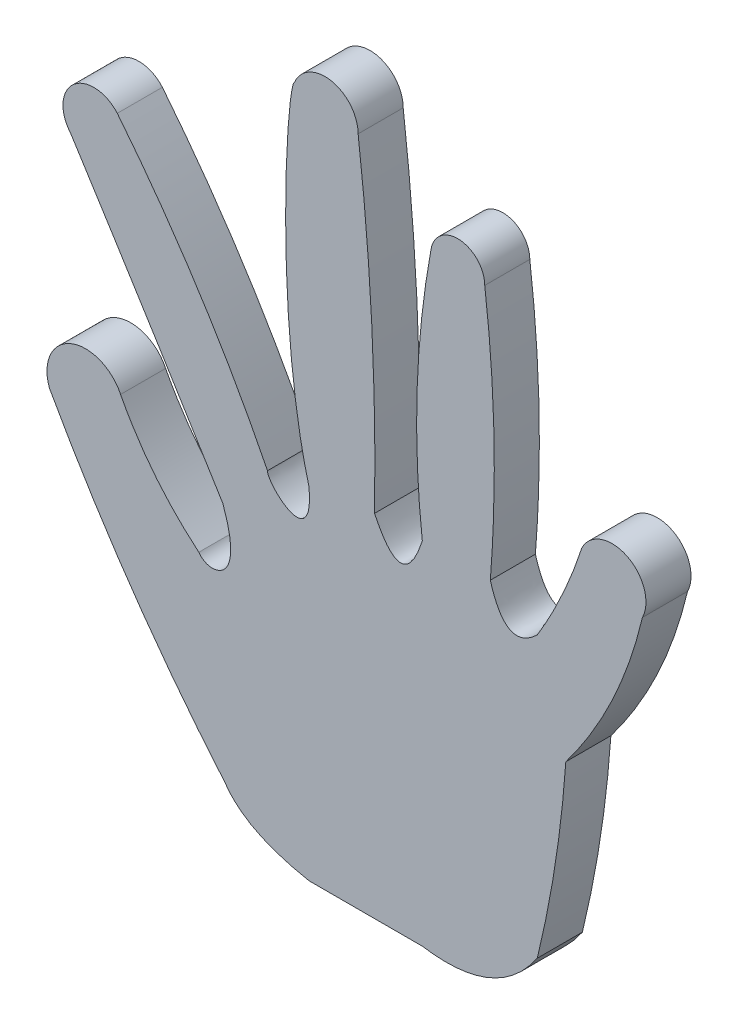
SolidWorks part; units mm, degrees
ref_plane "Alzado" through (0, 0, 0) normal (0, 0, 1) x (1, 0, 0)
ref_plane "Planta" through (0, 0, 0) normal (0, 1, 0) x (1, 0, 0)
ref_plane "Vista lateral" through (0, 0, 0) normal (1, 0, 0) x (0, 0, -1)
sketch "Croquis1" plane through (0, 0, 0) normal (0, 0, 1) x (1, 0, 0)
  line L2 (6700.2438, -5767.9046) -> (6700.2438, -4928.6598)
  line L4 (379.8796, -6850.5261) -> (423.4568, -6912.9739)
  line L11 (6128.0168, 5985.3068) -> (6128.0168, 5601.9321)
  line L12 (2230.7034, -7786.8151) -> (4743.0538, -7786.8151)
  arc A0 (-3529.5138, -1202.2335) -> (-1951.8181, -532.5527) centre (-2727.0904, -899.3757) cw
  arc A1 (-3063.1145, 3936.7407) -> (-2024.3345, 4833.6116) centre (-2543.7245, 4385.1762) cw
  arc A2 (1907.6748, 7398.1559) -> (3318.7775, 7110.1003) centre (2583.665, 7109.3167) cw
  arc A3 (4937.6033, 5708.7587) -> (6128.0168, 5601.9321) centre (5528.0168, 5601.9321) cw
  arc A4 (8283.2924, 1638.8146) -> (9626.3211, 970.7772) centre (8954.8068, 1304.7959) cw
  arc A5 (-216.138, -2695.3683) -> (389.7191, -2690.6828) centre (85.1825, -2485.1012) ccw
  parabola Q0 (1307.8944, -368.1416) -> (-2024.3345, 4833.6116) focus (-12498.1898, -5525.2093) apex (-237.4606, 2347.6576) construction
  spline S0 degree 2 poles (316.998, -1491.0681) (625.9687, -2340.7163) (389.7191, -2690.6828) knots 0 0 0 0.430746 0.430746 0.430746
  spline S1 degree 2 poles (7292.1491, -532.5527) (6599.096, -1196.6311) (6251.6946, 0) knots 0 0 0 1 1 1
  spline S2 degree 2 poles (4743.0538, 0) (4312.7791, -1324.8214) (3682.75, 0) knots 0 0 0 1 1 1
  spline S3 degree 3 poles (2230.7034, -225.2212) (2353.6239, -1570.0471) (1307.5356, -636.8446) (1307.8944, -368.1416) knots 0 0 0 0 1 1 1 1
  spline S4 degree 2 poles (7926.4035, -2651.0034) (7782.91, -4725.0883) (7294.0577, -6741.7727) knots 0 0 0 1 1 1
  spline S5 degree 2 poles (-3529.5138, -1202.2335) (-1856.0374, -4219.2232) (379.8796, -6850.5261) knots 0 0 0 1 1 1
  spline S6 degree 2 poles (316.998, -1491.0681) (-1349.2167, 1237.7013) (-3063.1145, 3936.7407) knots 0 0 0 1 1 1
  spline S7 degree 2 poles (1307.8944, -368.1416) (-82.1474, 2408.6936) (-2024.3345, 4833.6116) knots 0 0 0 1 1 1
  spline S8 degree 2 poles (3318.7775, 7110.1003) (3746.2513, 3568.2244) (3682.75, 0) knots 0 0 0 1 1 1
  spline S9 degree 3 poles (1907.6748, 7398.1559) (1727.3743, 7282.6997) (1453.8222, 2643.6832) (2230.7034, -225.2212) knots 0 0 0 0 1 1 1 1
  spline S10 degree 2 poles (6128.0168, 5601.9321) (6476.1303, 2805.1245) (6251.6946, 0) knots 0 0 0 1 1 1
  spline S11 degree 2 poles (4937.6033, 5708.7587) (4413.952, 2863.6668) (4743.0538, 0) knots 0 0 0 1 1 1
  spline S12 degree 2 poles (9626.3211, 970.7772) (9151.2478, -1031.316) (7926.4035, -2651.0034) knots 0 0 0 1 1 1
  spline S13 degree 2 poles (8283.2924, 1638.8146) (7913.6817, 496.9997) (7292.1491, -532.5527) knots 0 0 0 1 1 1
  spline S14 degree 2 poles (-216.138, -2695.3683) (-1298.9067, -1787.8361) (-1951.8181, -532.5527) knots 0 0 0 1 1 1
  spline S15 degree 2 poles (7294.0577, -6741.7727) (6406.5177, -8048.245) (4743.0538, -7786.8151) knots 0 0 0 1 1 1
  spline S16 degree 2 poles (2230.7034, -7786.8151) (838.8771, -7523.1599) (379.8796, -6850.5261) knots 0 0 0 1 1 1
  point P44 (0, 0)
  point P45 (5528.0168, -8046.0527)
  point P46 (4937.6033, -8288.2431)
  point P47 (0, 0)
  point P48 (4743.0538, -7786.8151)
  point P49 (6487.0387, -7520.4239)
  point P51 (0, 0)
  point P52 (0, 0)
  point P53 (0, 0)
  point P54 (0, 0)
  dimension "D1" = 367.4321
  dimension "D2" = 600
sketch "Croquis2" plane through (0, 0, 0) normal (0, 0, 1) x (1, 0, 0)
  spline S0 degree 2 poles (1307.8944, -368.1416) (-82.7392, 2409.6269) (-2024.3345, 4833.6116) knots 0 0 0 1 1 1
extrude "Saliente-Extruir2" add sketch "Croquis1" along normal blind 1000
